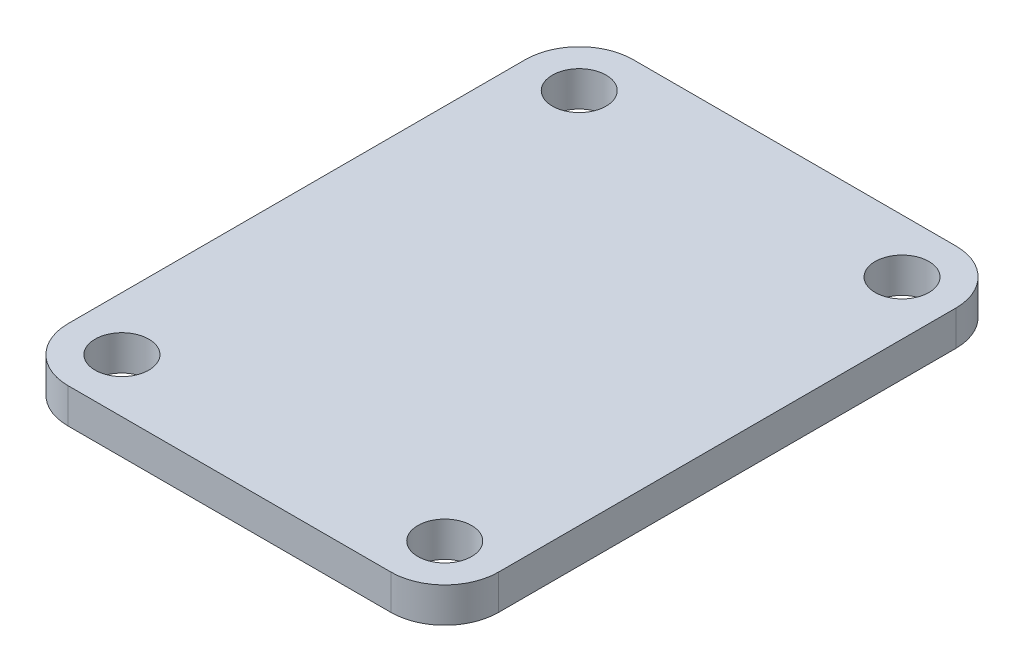
SolidWorks part; units mm, degrees
ref_plane "Front Plane" through (0, 0, 0) normal (0, 0, 1) x (1, 0, 0)
ref_plane "Top Plane" through (0, 0, 0) normal (0, 1, 0) x (1, 0, 0)
ref_plane "Right Plane" through (0, 0, 0) normal (1, 0, 0) x (0, 0, -1)
sketch "Sketch1" plane through (0, 0, 0) normal (0, 1, 0) x (1, 0, 0)
  line L1 (10.16, -13.335) -> (-10.16, -13.335)
  line L2 (10.16, -13.335) -> (10.16, 13.335)
  line L3 (10.16, 13.335) -> (-10.16, 13.335)
  line L4 (-10.16, -13.335) -> (-10.16, 13.335)
  line L5 (10.16, -13.335) -> (-10.16, 13.335) construction
  line L6 (10.16, 13.335) -> (-10.16, -13.335) construction
  line L7 (7.62, -10.795) -> (-7.62, -10.795) construction
  line L8 (7.62, -10.795) -> (7.62, 10.795) construction
  line L9 (7.62, 10.795) -> (-7.62, 10.795) construction
  line L10 (-7.62, -10.795) -> (-7.62, 10.795) construction
  line L11 (7.62, -10.795) -> (-7.62, 10.795) construction
  line L12 (7.62, 10.795) -> (-7.62, -10.795) construction
  circle A0 centre (-7.62, 10.795) radius 1.27
  circle A1 centre (7.62, 10.795) radius 1.27
  circle A2 centre (7.62, -10.795) radius 1.27
  circle A3 centre (-7.62, -10.795) radius 1.27
  point P0 (0, 0)
  point P6 (0, 0)
  dimension "D5" = 2.54
  dimension "D1" = 20.32
  dimension "D2" = 26.67
  dimension "D3" = 15.24
  dimension "D4" = 21.59
extrude "Boss-Extrude1" add sketch "Sketch1" along normal blind 1.651
fillet "Fillet1" radius 2.54 4 edges at (10.16, 0.8255, -13.335) (-10.16, 0.8255, -13.335) (-10.16, 0.8255, 13.335) (10.16, 0.8255, 13.335)
